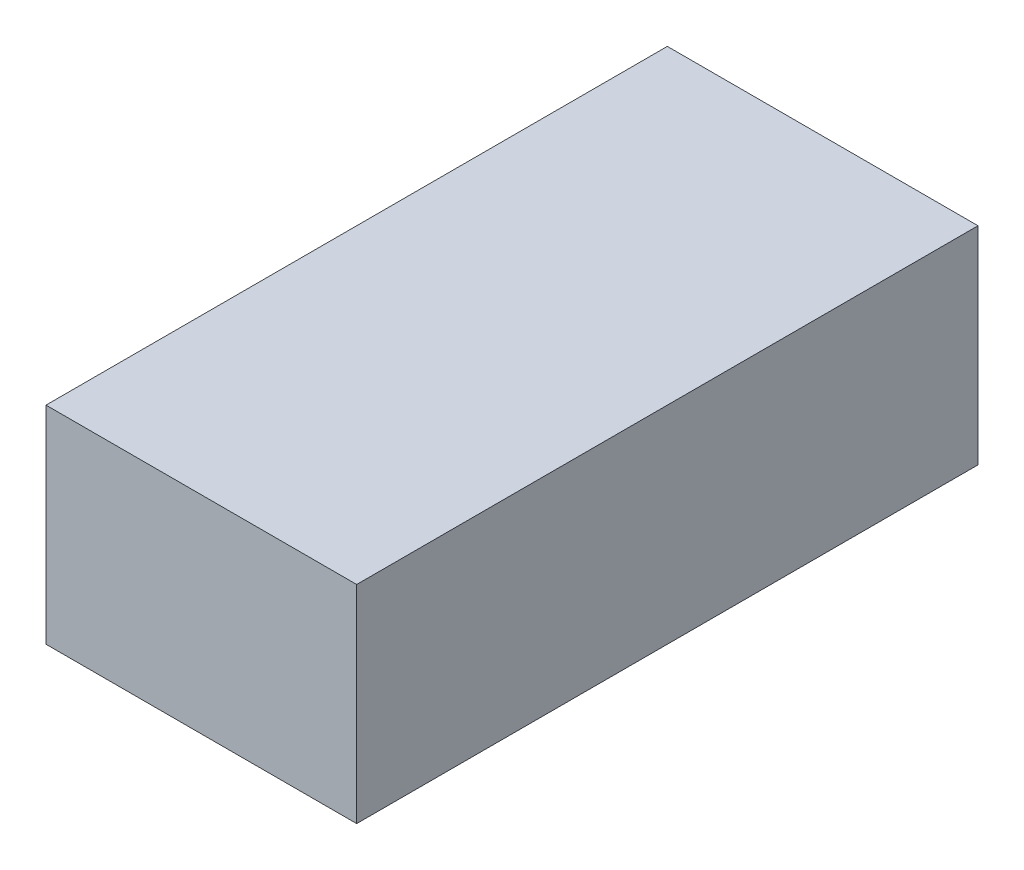
SolidWorks part; units mm, degrees
ref_plane "Front Plane" through (0, 0, 0) normal (0, 0, 1) x (1, 0, 0)
ref_plane "Top Plane" through (0, 0, 0) normal (0, 1, 0) x (1, 0, 0)
ref_plane "Right Plane" through (0, 0, 0) normal (1, 0, 0) x (0, 0, -1)
sketch "Sketch1" plane through (0, 0, 0) normal (0, 0, 1) x (1, 0, 0)
  line L1 (-25, 14.876) -> (5, 14.876)
  line L2 (-25, 14.876) -> (-25, -5.124)
  line L3 (-25, -5.124) -> (5, -5.124)
  line L4 (5, 14.876) -> (5, -5.124)
  point P0 (0, 0)
  dimension "Width" = 30
  dimension "Depth" = 20
extrude "Boss-Extrude1" add sketch "Sketch1" along normal blind 60
sketch "Sketch2" plane through (0, 14.876, 0) normal (0, 1, 0) x (1, 0, 0)
  circle A0 centre (-13.8041, -21.0662) radius 10
  dimension "D1" = 20
equation "\"Depth@Sketch1\"=\"Width@Sketch1\" /2+5"
equation "\"Length@Boss-Extrude1\" = \"Width@Sketch1\" * 2"
equation "\"Width@Sketch1\"= \"A\""
equation "\"A\"= 30mm"
equation "\"B\"= 2mm"
